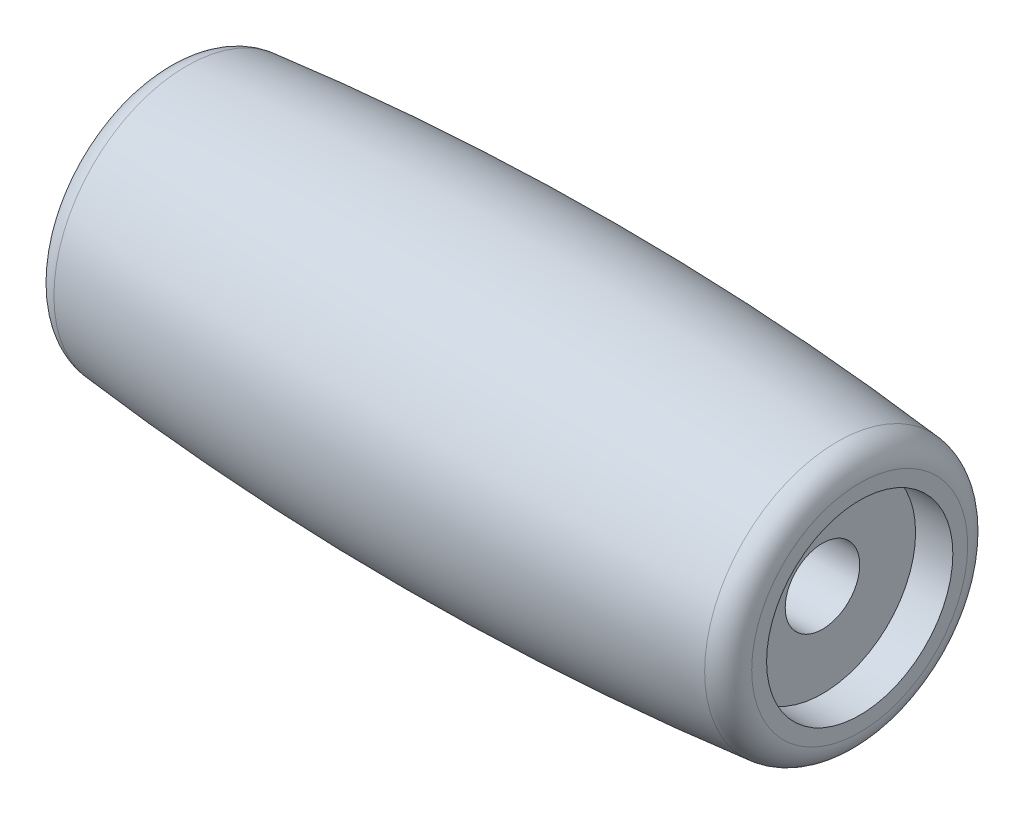
SolidWorks part; units mm, degrees
ref_plane "Front Plane" through (0, 0, 0) normal (0, 0, 1) x (1, 0, 0)
ref_plane "Top Plane" through (0, 0, 0) normal (0, 1, 0) x (1, 0, 0)
ref_plane "Right Plane" through (0, 0, 0) normal (1, 0, 0) x (0, 0, -1)
sketch "Sketch1" plane through (0, 0, 0) normal (0, 0, 1) x (1, 0, 0)
  line L0 (0, 0) -> (0, 6) construction
  line L1 (0, 0) -> (11.7801, 0) construction
  line L2 (-12.5, 1.5) -> (12.5, 1.5)
  line L3 (12.5, 1.5) -> (12.5, 3.75)
  line L4 (12.5, 3.75) -> (14, 3.75)
  line L5 (14, 3.75) -> (14, 4.3486)
  line L6 (-14, 3.75) -> (-14, 4.3486)
  line L7 (-12.5, 3.75) -> (-14, 3.75)
  line L8 (-12.5, 1.5) -> (-12.5, 3.75)
  arc A0 (-13.1, 5.3436) -> (13.1, 5.3436) centre (0, -125.0417) cw
  arc A1 (14, 4.3486) -> (13.1, 5.3436) centre (13, 4.3486) ccw
  arc A2 (-14, 4.3486) -> (-13.1, 5.3436) centre (-13, 4.3486) cw
  point P13 (0, 1.5)
  point P18 (14, 5.25)
  point P21 (-14, 5.25)
  dimension "D7" = 1
  dimension "D1" = 1.5
  dimension "D2" = 3.75
  dimension "D3" = 1.5
  dimension "D4" = 1.5
  dimension "D5" = 14
  dimension "D6" = 6
revolve "Revolve1" add sketch "Sketch1" angle 360 about L1
